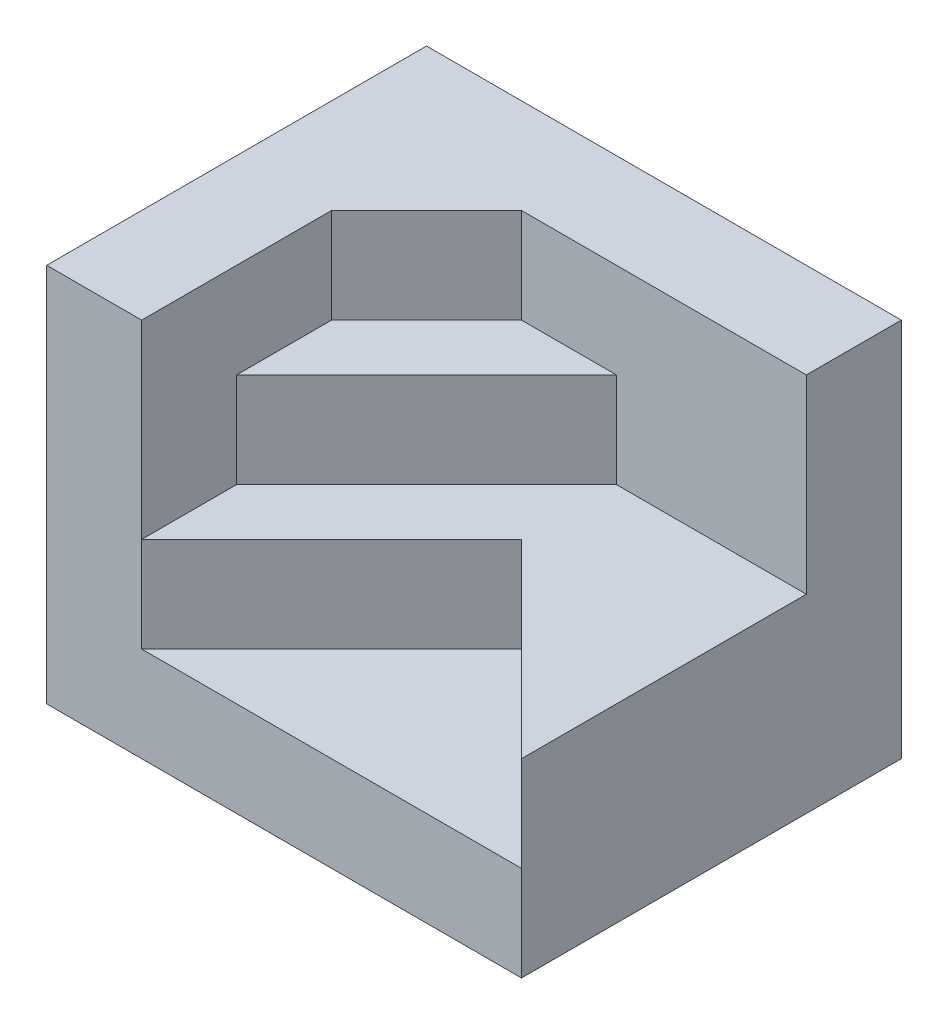
SolidWorks part; units mm, degrees
ref_plane "前基準面" through (0, 0, 0) normal (0, 0, 1) x (1, 0, 0)
ref_plane "上基準面" through (0, 0, 0) normal (0, 1, 0) x (1, 0, 0)
ref_plane "右基準面" through (0, 0, 0) normal (1, 0, 0) x (0, 0, -1)
sketch "草圖1" plane through (0, 0, 0) normal (0, 0, 1) x (1, 0, 0)
  line L1 (0, 0) -> (25, 0)
  line L2 (0, 0) -> (0, -20)
  line L3 (0, -20) -> (25, -20)
  line L4 (25, 0) -> (25, -20)
  dimension "D1" = 20
  dimension "D2" = 25
extrude "填料-伸長1" add sketch "草圖1" against normal blind 20 contours L1 L4 L3 L2
sketch "草圖2" plane through (0, 0, 0) normal (0, 1, 0) x (1, 0, 0)
  line L0 (0, 20) -> (25, 20) construction
  line L1 (0, 0) -> (5, 0)
  line L2 (0, 0) -> (0, 20) construction
  line L3 (0, 20) -> (5, 20) construction
  line L4 (5, 0) -> (5, 20) construction
  line L5 (10, 15) -> (5, 10)
  line L6 (25, 20) -> (0, 20) construction
  line L7 (25, 20) -> (25, 15)
  line L8 (25, 15) -> (0, 15) construction
  line L9 (0, 20) -> (0, 15) construction
  line L10 (5, 15) -> (10, 15) construction
  line L11 (5, 15) -> (5, 10) construction
  line L12 (5, 10) -> (10, 10) construction
  line L13 (10, 15) -> (10, 10) construction
  line L14 (15, 15) -> (5, 5)
  line L15 (10, 15) -> (15, 15)
  line L16 (5, 10) -> (5, 5)
  line L17 (5, 5) -> (4.9141, 5.0962)
  point P10 (5, 15)
  dimension "D1" = 5
  dimension "D2" = 5
  dimension "D3" = 5
  dimension "D4" = 5
  dimension "D5" = 5
extrude "除料-伸長1" cut sketch "草圖2" against normal blind 5 contours L5 L16 L14 L15
sketch "草圖3" plane through (0, 0, 0) normal (0, 1, 0) x (1, 0, 0)
  line L0 (15, 15) -> (5, 5) construction
  line L1 (15, 15) -> (5, 5)
  line L2 (15, 15) -> (25, 15)
  line L3 (25, 20) -> (25, 0) construction
  line L4 (25, 15) -> (25, 0)
  line L5 (25, 0) -> (5, 0)
  line L6 (0, 0) -> (25, 0) construction
  line L7 (5, 0) -> (5, 5)
extrude "除料-伸長2" cut sketch "草圖3" against normal blind 10
sketch "草圖4" plane through (0, -10, 0) normal (0, 1, 0) x (1, 0, 0)
  line L0 (5, 0) -> (15, 10)
  line L1 (15, 10) -> (25, 0)
  line L2 (5, 0) -> (25, 0) construction
  line L3 (5, 0) -> (25, 0)
  dimension "D1" = 45
  dimension "D2" = 10
extrude "除料-伸長3" cut sketch "草圖4" against normal blind 5
